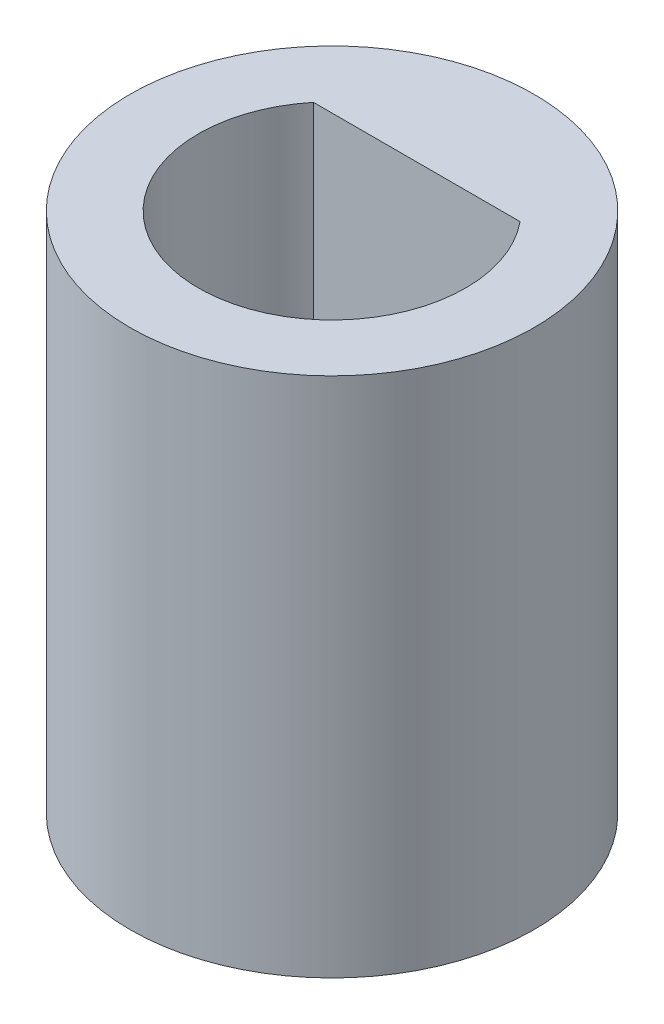
SolidWorks part; units mm, degrees
ref_plane "Front Plane" through (0, 0, 0) normal (0, 0, 1) x (1, 0, 0)
ref_plane "Top Plane" through (0, 0, 0) normal (0, 1, 0) x (1, 0, 0)
ref_plane "Right Plane" through (0, 0, 0) normal (1, 0, 0) x (0, 0, -1)
sketch "Sketch1" plane through (0, 0, 0) normal (0, 1, 0) x (1, 0, 0)
  line L0 (-1.5851, 1.3) -> (1.5851, 1.3)
  circle A0 centre (0, 0) radius 2.05
  circle A1 centre (0, 0) radius 3.1
  dimension "D1" = 4.1
  dimension "D2" = 6.2
  dimension "D3" = 1.3
extrude "Boss-Extrude1" add sketch "Sketch1" along normal blind 8 contours A1 A0 | L0 A0
